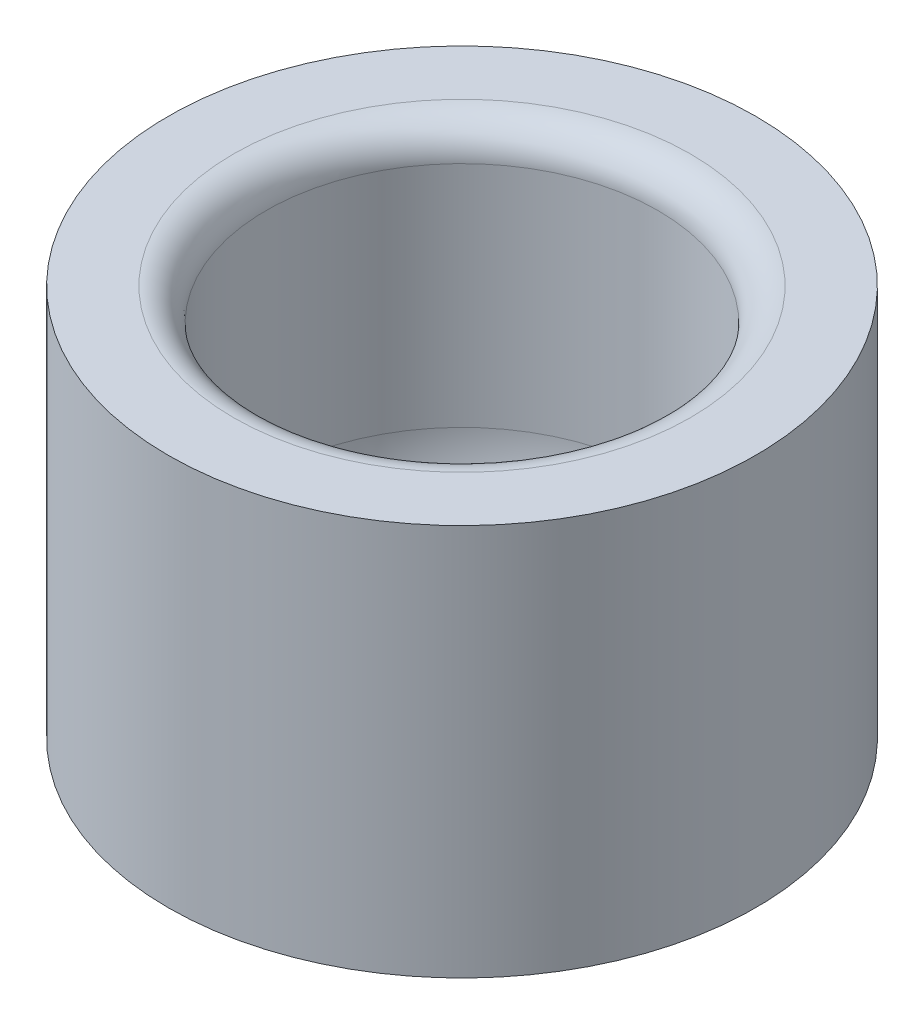
SolidWorks part; units mm, degrees
ref_plane "Front Plane" through (0, 0, 0) normal (0, 0, 1) x (1, 0, 0)
ref_plane "Top Plane" through (0, 0, 0) normal (0, 1, 0) x (1, 0, 0)
ref_plane "Right Plane" through (0, 0, 0) normal (1, 0, 0) x (0, 0, -1)
sketch "Sketch1" plane through (0, 0, 0) normal (0, 1, 0) x (1, 0, 0)
  circle A0 centre (0, 0) radius 9
  dimension "D1" = 18
extrude "Boss-Extrude1" add sketch "Sketch1" along normal blind 16.4
hole_wizard "Ø12.0mm Dowel Hole1" positions "3DSketch2" profile "Sketch2" hole size "Ø12.0" standard "ANSI Metric"
sketch3d "3DSketch2"
  line L0 (0, 16.4, 0) -> (0, 16.4, 11.3429) construction
  line L1 (0, 16.4, 0) -> (0, 0, 0) construction
  point P0 (0, 0, 0)
  point P4 (0, 16.4, 0)
sketch "Sketch2" plane through (0, 16.4, 0) normal (1, 0, 0) x (0, 0, 1)
  line L0 (0, 0) -> (0, 13)
  line L1 (0, 13) -> (6, 13)
  line L2 (6, 13) -> (6, 0)
  line L5 (6, 0) -> (0, 0)
  line L10 (0, 13) -> (-6, 13) construction
  line L11 (0, -2.9326) -> (0, 107.95) construction
  dimension "Hole Dia." = 12
  dimension "Hole Depth" = 13
  dimension "Drill Angle" = 180
sketch "Sketch3" plane through (0, 0, 0) normal (1, 0, 0) x (0, 0, -1)
  line L0 (-9, 4.8044) -> (-1.0041, 0) construction
  line L2 (0, 0) -> (0, 25.3828) construction
  line L3 (-9, 0) -> (9, 0) construction
  line L4 (-9, 4.8044) -> (-1.0041, 0) construction
  line L5 (-9, 0) -> (-1.6864, 0)
  line L6 (-9, 4.3944) -> (-1.6864, 0)
  line L10 (-9, 0) -> (-9, 4.3944)
  dimension "D1" = 0.41
  dimension "D2" = 59
revolve "Cut-Revolve1" cut sketch "Sketch3" angle 360 about L2
fillet "Fillet1" radius 5 1 edges at (0, 3.4, 6)
fillet "Fillet2" radius 1 1 edges at (0, 16.4, 6)
